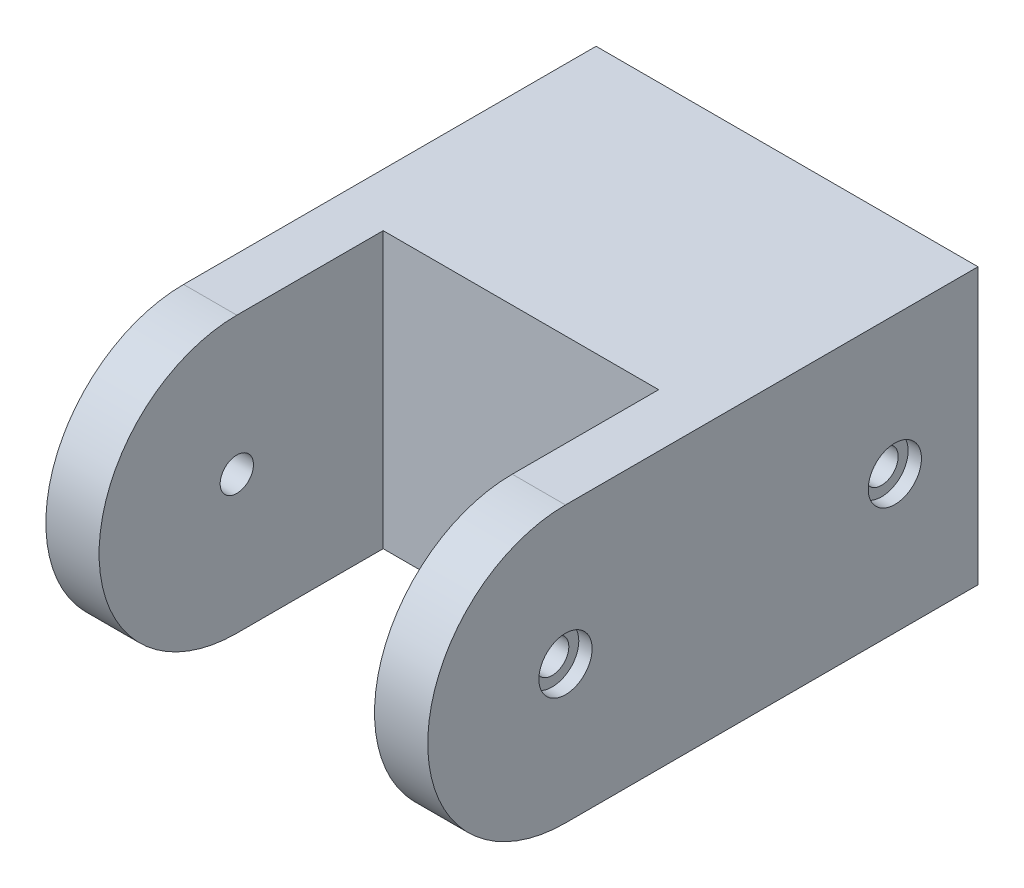
SolidWorks part; units mm, degrees
ref_plane "Front Plane" through (0, 0, 0) normal (0, 0, 1) x (1, 0, 0)
ref_plane "Top Plane" through (0, 0, 0) normal (0, 1, 0) x (1, 0, 0)
ref_plane "Right Plane" through (0, 0, 0) normal (1, 0, 0) x (0, 0, -1)
sketch "Sketch1" plane through (0, 0, 0) normal (0, 0, 1) x (1, 0, 0)
  line L1 (-12.7, 12.7) -> (12.7, 12.7)
  line L2 (-12.7, 12.7) -> (-12.7, -12.7)
  line L3 (-12.7, -12.7) -> (12.7, -12.7)
  line L4 (12.7, 12.7) -> (12.7, -12.7)
  line L5 (-12.7, 12.7) -> (12.7, -12.7) construction
  line L6 (-12.7, -12.7) -> (12.7, 12.7) construction
  line L7 (-28.7, 20.7) -> (28.7, 20.7)
  line L8 (-28.7, 20.7) -> (-28.7, -20.7)
  line L9 (-28.7, -20.7) -> (28.7, -20.7)
  line L10 (28.7, 20.7) -> (28.7, -20.7)
  line L11 (-28.7, 20.7) -> (28.7, -20.7) construction
  line L12 (-28.7, -20.7) -> (28.7, 20.7) construction
  point P0 (0, 0)
  point P6 (0, 0)
  dimension "D1" = 25.4
  dimension "D2" = 25.4
  dimension "D3" = 16
  dimension "D4" = 8
  dimension "D5" = 8
extrude "Boss-Extrude1" add sketch "Sketch1" along normal blind 30
sketch "Sketch2" plane through (0, 0, 30) normal (0, 0, 1) x (1, 0, 0)
  line L5 (-28.7, 20.7) -> (28.7, 20.7)
  line L6 (-28.7, 20.7) -> (-28.7, -20.7)
  line L7 (-28.7, -20.7) -> (28.7, -20.7)
  line L8 (28.7, 20.7) -> (28.7, -20.7)
  line L9 (-28.7, 20.7) -> (28.7, -20.7) construction
  line L10 (-28.7, -20.7) -> (28.7, 20.7) construction
  point P0 (0, 0)
  point P1 (0, 0)
extrude "Boss-Extrude2" add sketch "Sketch2" along normal blind 10
sketch "Sketch4" plane through (28.7, 0, 0) normal (1, 0, 0) x (0, 0, -1)
  line L0 (-40, -20.7) -> (0, -20.7) construction
  line L1 (-40, -20.7) -> (-40, 20.7)
  line L2 (-40, 20.7) -> (-62, 20.7)
  line L3 (-40, -20.7) -> (-62, -20.7)
  arc A1 (-62, -20.7) -> (-62, 20.7) centre (-62, 0) cw
  dimension "D1" = 22
extrude "Boss-Extrude3" add sketch "Sketch4" against normal blind 8
sketch "Sketch5" plane through (-28.7, 0, 0) normal (-1, 0, 0) x (0, 0, 1)
  line L0 (40, 20.7) -> (40, -20.7)
  line L1 (40, -20.7) -> (62, -20.7)
  line L2 (40, 20.7) -> (62, 20.7)
  arc A0 (62, 20.7) -> (62, -20.7) centre (62, 0) cw
extrude "Boss-Extrude4" add sketch "Sketch5" against normal blind 8
sketch "Sketch6" plane through (28.7, 0, 0) normal (1, 0, 0) x (0, 0, -1)
  circle A0 centre (-62, 0) radius 2.5
  dimension "D1" = 5
extrude "Cut-Extrude1" cut sketch "Sketch6" against normal up to surface (57.4 mm away) up to face at (-28.7, 0, 36.175)
sketch "Sketch9" plane through (28.7, 0, 0) normal (1, 0, 0) x (0, 0, -1)
  line L0 (0, -20.7) -> (0, 20.7) construction
  circle A0 centre (-12.5, 0) radius 2.5
  dimension "D1" = 5
  dimension "D2" = 12.5
extrude "Cut-Extrude4" cut sketch "Sketch9" against normal up to surface (57.4 mm away) up to face at (-28.7, 0, 59.5)
sketch "Sketch7" plane through (-28.7, 0, 0) normal (-1, 0, 0) x (0, 0, 1)
  circle A0 centre (62, 0) radius 4
  circle A1 centre (12.5, 0) radius 4
  dimension "D1" = 8
  dimension "D2" = 8
extrude "Cut-Extrude2" cut sketch "Sketch7" against normal blind 2
sketch "Sketch8" plane through (28.7, 0, 0) normal (1, 0, 0) x (0, 0, -1)
  circle A0 centre (-62, 0) radius 4
  circle A1 centre (-12.5, 0) radius 4
  dimension "D1" = 8
  dimension "D2" = 8
extrude "Cut-Extrude3" cut sketch "Sketch8" against normal blind 2
